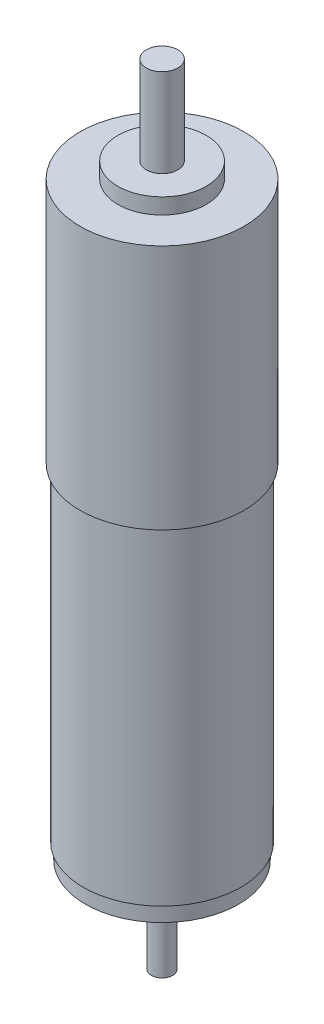
SolidWorks part; units mm, degrees
ref_plane "Face" through (0, 0, 0) normal (0, 0, 1) x (1, 0, 0)
ref_plane "Dessus" through (0, 0, 0) normal (0, 1, 0) x (1, 0, 0)
ref_plane "Droite" through (0, 0, 0) normal (1, 0, 0) x (0, 0, -1)
sketch "Esquisse1" plane through (0, 0, 0) normal (0, 0, 1) x (1, 0, 0)
  line L0 (0, 0) -> (0, 110) construction
  line L1 (0, 0) -> (12.15, 0)
  line L2 (12.15, 0) -> (12.15, 2.5)
  line L3 (12.15, 2.5) -> (12.5, 2.5)
  line L4 (12.5, 2.5) -> (12.5, 54.5)
  line L5 (12.5, 54.5) -> (13, 54.5)
  line L6 (13, 54.5) -> (13, 93.5)
  line L7 (13, 93.5) -> (7, 93.5)
  line L8 (7, 93.5) -> (7, 96)
  line L9 (7, 96) -> (2.5, 96)
  line L10 (2.5, 96) -> (2.5, 110)
  line L11 (2.5, 110) -> (0, 110)
  line L12 (0, 0) -> (0, 110)
  dimension "D1" = 5
  dimension "D2" = 25
  dimension "D3" = 26
  dimension "D4" = 54.5
  dimension "D5" = 14
  dimension "D6" = 14
  dimension "D7" = 2.5
  dimension "D8" = 39
  dimension "D9" = 24.3
  dimension "D10" = 2.5
revolve "Révolution1" add sketch "Esquisse1" angle 360 about L0
sketch "Esquisse2" plane through (0, 0, 0) normal (0, -1, 0) x (1, 0, 0)
  circle A0 centre (0, 0) radius 1.6928
extrude "Boss.-Extru.1" add sketch "Esquisse2" along normal blind 15
sketch "Esquisse3" plane through (0, 0, 0) normal (0, -1, 0) x (1, 0, 0)
  circle A0 centre (0, 0) radius 4
  dimension "D1" = 8
extrude "Boss.-Extru.2" add sketch "Esquisse3" along normal blind 2.5
